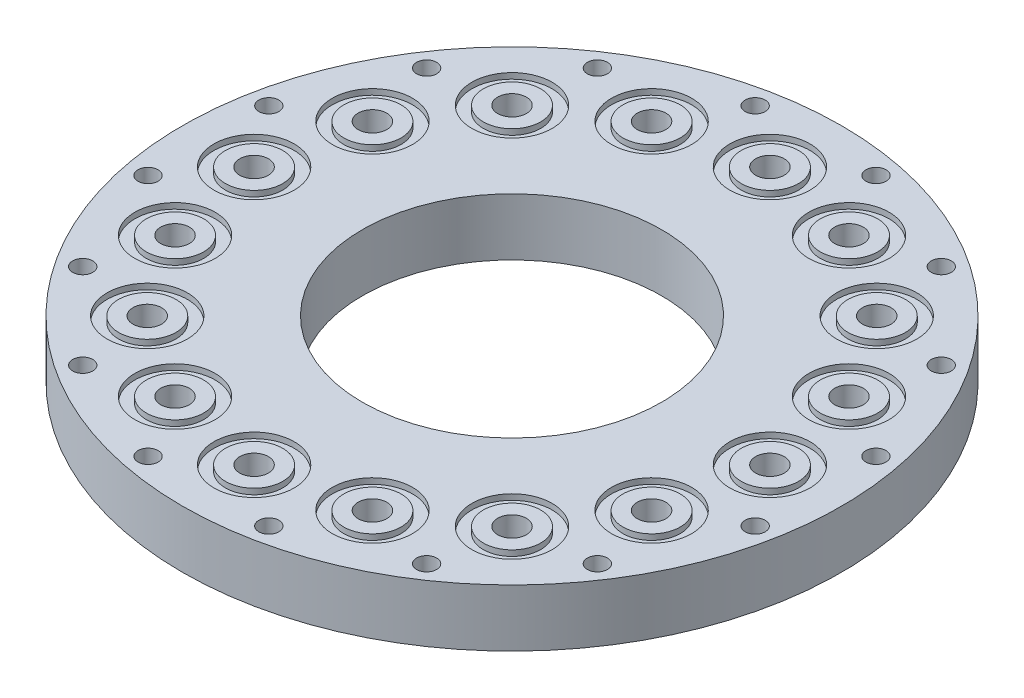
SolidWorks part; units mm, degrees
other "Markup1"
sketch "Sketch3" plane through (-57.5, 10, 57.5) normal (-0.8509, 0.162, 0.4998) x (0.3514, 0.8827, 0.3121)
ref_plane "Front Plane" through (0, 0, 0) normal (0, 0, 1) x (1, 0, 0)
ref_plane "Top Plane" through (0, 0, 0) normal (0, 1, 0) x (1, 0, 0)
ref_plane "Right Plane" through (0, 0, 0) normal (1, 0, 0) x (0, 0, -1)
sketch "Sketch1" plane through (0, 0, 0) normal (0, 1, 0) x (1, 0, 0)
  line L0 (-10.5349, 52.9624) -> (0, 0) construction
  line L1 (0, 0) -> (62.7639, 0) construction
  line L2 (-17.2208, 41.5746) -> (0, 0) construction
  line L3 (0, 0) -> (0, 45) construction
  circle A0 centre (0, 0) radius 57.5
  circle A1 centre (0, 0) radius 54 construction
  circle A2 centre (-10.5349, 52.9624) radius 1.75
  circle A3 centre (10.5349, 52.9624) radius 1.75
  circle A4 centre (30.0008, 44.8994) radius 1.75
  circle A5 centre (44.8994, 30.0008) radius 1.75
  circle A6 centre (52.9624, 10.5349) radius 1.75
  circle A7 centre (52.9624, -10.5349) radius 1.75
  circle A8 centre (44.8994, -30.0008) radius 1.75
  circle A9 centre (30.0008, -44.8994) radius 1.75
  circle A10 centre (10.5349, -52.9624) radius 1.75
  circle A11 centre (-10.5349, -52.9624) radius 1.75
  circle A12 centre (-30.0008, -44.8994) radius 1.75
  circle A13 centre (-44.8994, -30.0008) radius 1.75
  circle A14 centre (0, 0) radius 26.1
  circle A15 centre (0, 0) radius 45 construction
  circle A16 centre (0, 45) radius 2.5
  circle A17 centre (17.2208, 41.5746) radius 2.5
  circle A18 centre (31.8198, 31.8198) radius 2.5
  circle A19 centre (41.5746, 17.2208) radius 2.5
  circle A20 centre (45, 0) radius 2.5
  circle A21 centre (41.5746, -17.2208) radius 2.5
  circle A22 centre (31.8198, -31.8198) radius 2.5
  circle A23 centre (17.2208, -41.5746) radius 2.5
  circle A24 centre (0, -45) radius 2.5
  circle A25 centre (-17.2208, -41.5746) radius 2.5
  circle A26 centre (-31.8198, -31.8198) radius 2.5
  circle A27 centre (-41.5746, -17.2208) radius 2.5
  circle A28 centre (-45, 0) radius 2.5
  circle A29 centre (-41.5746, 17.2208) radius 2.5
  circle A30 centre (-31.8198, 31.8198) radius 2.5
  circle A31 centre (-17.2208, 41.5746) radius 2.5
  circle A32 centre (-52.9624, -10.5349) radius 1.75
  circle A33 centre (-52.9624, 10.5349) radius 1.75
  circle A34 centre (-44.8994, 30.0008) radius 1.75
  circle A35 centre (-30.0008, 44.8994) radius 1.75
  point P31 (0, 0)
  point P55 (0, 0)
  dimension "D1" = 115
  dimension "D2" = 108
  dimension "D3" = 3.5
  dimension "D4" = 52.2
  dimension "D5" = 90
  dimension "D6" = 5
  dimension "D9" = 11.25
  dimension "D10" = 11.25
  dimension "D8" = 16
  dimension "D7" = 16
extrude "Boss-Extrude1" add sketch "Sketch1" along normal blind 10
sketch "Sketch2" plane through (0, 10, 0) normal (0, 1, 0) x (1, 0, 0)
  circle A0 centre (0, 0) radius 45 construction
  circle A1 centre (0, 45) radius 7
  circle A2 centre (17.2208, 41.5746) radius 7
  circle A3 centre (31.8198, 31.8198) radius 7
  circle A4 centre (41.5746, 17.2208) radius 7
  circle A5 centre (45, 0) radius 7
  circle A6 centre (41.5746, -17.2208) radius 7
  circle A7 centre (31.8198, -31.8198) radius 7
  circle A8 centre (17.2208, -41.5746) radius 7
  circle A9 centre (0, -45) radius 7
  circle A10 centre (-17.2208, -41.5746) radius 7
  circle A11 centre (-31.8198, -31.8198) radius 7
  circle A12 centre (0, 45) radius 5
  circle A13 centre (17.2208, 41.5746) radius 5
  circle A14 centre (31.8198, 31.8198) radius 5
  circle A15 centre (41.5746, 17.2208) radius 5
  circle A16 centre (45, 0) radius 5
  circle A17 centre (41.5746, -17.2208) radius 5
  circle A18 centre (31.8198, -31.8198) radius 5
  circle A19 centre (17.2208, -41.5746) radius 5
  circle A20 centre (0, -45) radius 5
  circle A21 centre (-17.2208, -41.5746) radius 5
  circle A22 centre (-31.8198, -31.8198) radius 5
  circle A23 centre (-41.5746, -17.2208) radius 5
  circle A24 centre (-45, 0) radius 5
  circle A25 centre (-41.5746, 17.2208) radius 5
  circle A26 centre (-31.8198, 31.8198) radius 5
  circle A27 centre (-17.2208, 41.5746) radius 5
  circle A28 centre (-41.5746, -17.2208) radius 7
  circle A29 centre (-45, 0) radius 7
  circle A30 centre (-41.5746, 17.2208) radius 7
  circle A31 centre (-31.8198, 31.8198) radius 7
  circle A32 centre (-17.2208, 41.5746) radius 7
  point P28 (0, 0)
  point P51 (0, 0)
  dimension "D1" = 14
  dimension "D3" = 10
  dimension "D2" = 16
  dimension "D4" = 16
extrude "Cut-Extrude1" cut sketch "Sketch2" against normal blind 1
